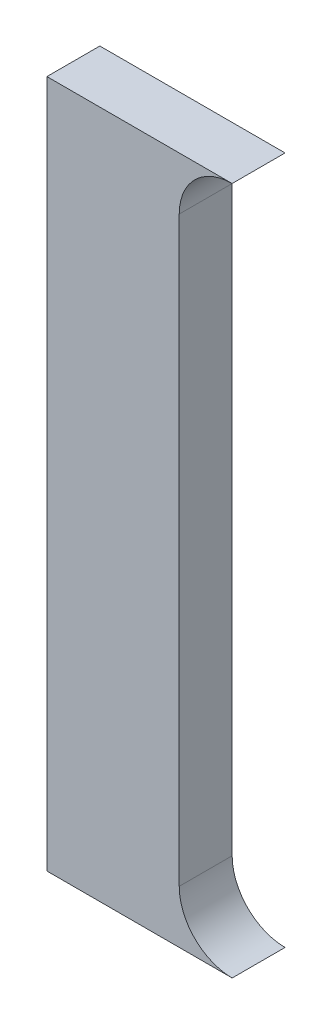
SolidWorks part; units mm, degrees
material "MDF"
ref_plane "Front Plane" through (0, 0, 0) normal (0, 0, 1) x (1, 0, 0)
ref_plane "Top Plane" through (0, 0, 0) normal (0, 1, 0) x (1, 0, 0)
ref_plane "Right Plane" through (0, 0, 0) normal (1, 0, 0) x (0, 0, -1)
sketch "Sketch1" plane through (0, 0, 0) normal (0, 0, 1) x (1, 0, 0)
  line L1 (-15.875, -82.55) -> (15.875, -82.55)
  line L2 (-15.875, -82.55) -> (-15.875, 82.55)
  line L3 (-15.875, 82.55) -> (15.875, 82.55)
  line L4 (15.875, -82.55) -> (15.875, 82.55)
  line L5 (-15.875, -82.55) -> (15.875, 82.55) construction
  line L6 (-15.875, 82.55) -> (15.875, -82.55) construction
  point P0 (0, 0)
  dimension "D1" = 31.75
  dimension "D2" = 165.1
extrude "Boss-Extrude1" add sketch "Sketch1" along normal blind 12.7
sketch "Sketch2" plane through (0, 0, 12.7) normal (0, 0, 1) x (1, 0, 0)
  line L0 (15.875, 82.55) -> (28.575, 82.55)
  line L1 (15.875, -82.55) -> (15.875, 82.55) construction
  line L2 (15.875, 82.55) -> (15.875, 69.85)
  line L3 (0, 0) -> (57.4414, 0) construction
  line L4 (15.875, -82.55) -> (15.875, -69.85)
  line L5 (15.875, -82.55) -> (28.575, -82.55)
  arc A0 (28.575, 82.55) -> (15.875, 69.85) centre (28.575, 69.85) ccw
  arc A1 (28.575, -82.55) -> (15.875, -69.85) centre (28.575, -69.85) cw
  dimension "D1" = 12.7
extrude "Boss-Extrude2" add sketch "Sketch2" against normal up to surface (12.7 mm away) up to face at (0, 0, 0)
